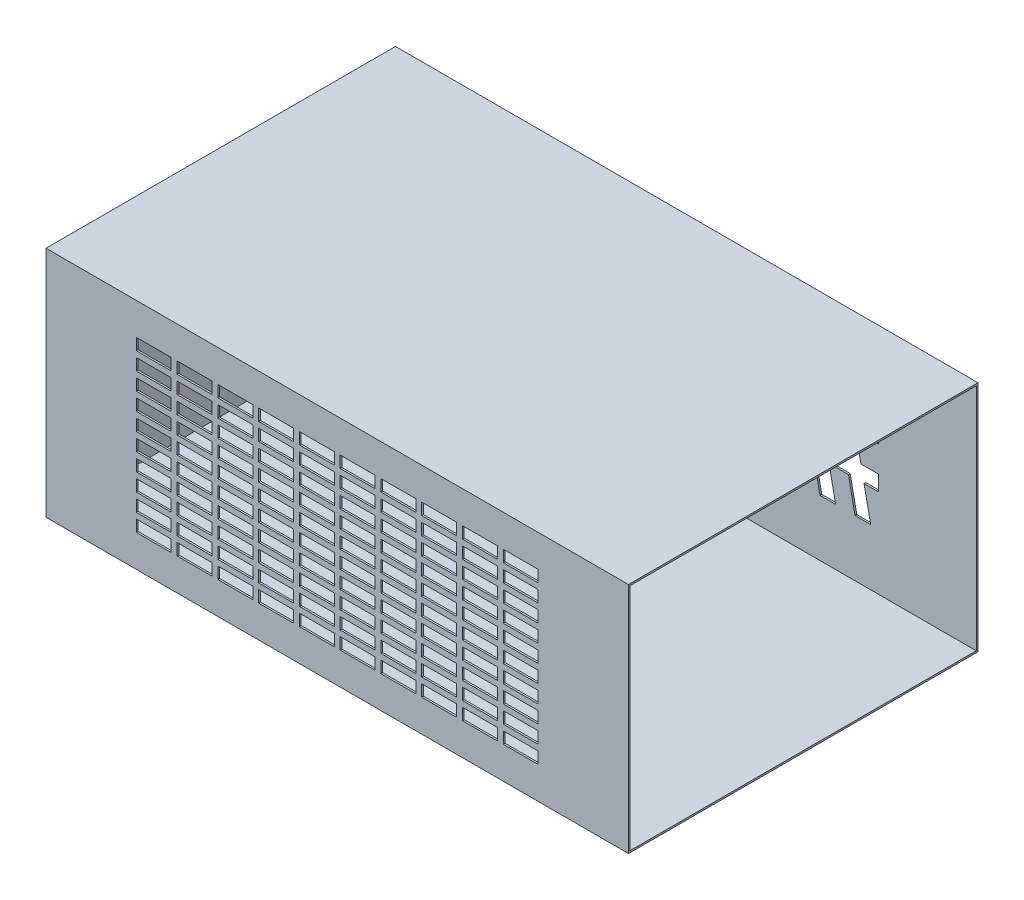
SolidWorks part; units mm, degrees
ref_plane "Спереди" through (0, 0, 0) normal (0, 0, 1) x (1, 0, 0)
ref_plane "Сверху" through (0, 0, 0) normal (0, 1, 0) x (1, 0, 0)
ref_plane "Справа" through (0, 0, 0) normal (1, 0, 0) x (0, 0, -1)
sketch "Эскиз1" plane through (0, 0, 0) normal (0, 0, 1) x (1, 0, 0)
  line L1 (250, -100) -> (-250, -100)
  line L2 (250, -100) -> (250, 100)
  line L3 (250, 100) -> (-250, 100)
  line L4 (-250, -100) -> (-250, 100)
  line L5 (250, -100) -> (-250, 100) construction
  line L6 (250, 100) -> (-250, -100) construction
  point P0 (0, 0)
  dimension "D1" = 500
  dimension "D2" = 200
extrude "Бобышка-Вытянуть2" add sketch "Эскиз1" along normal mid plane 300
shell "Оболочка3" thickness 1.5
sketch "Эскиз5" plane through (0, 0, 150) normal (0, 0, 1) x (1, 0, 0)
  line L0 (250, 100) -> (-250, 100) construction
  line L1 (-172.5, 72.5) -> (-142.5, 72.5)
  line L2 (-172.5, 72.5) -> (-172.5, 62.5)
  line L3 (-172.5, 62.5) -> (-142.5, 62.5)
  line L4 (-142.5, 72.5) -> (-142.5, 62.5)
  line L5 (-250, 100) -> (-250, -100) construction
  dimension "D1" = 30
  dimension "D2" = 10
  dimension "D3" = 27.5
  dimension "D4" = 77.5
extrude "Вырез-Вытянуть1" cut sketch "Эскиз5" against normal up to next
pattern_linear "Линейный массив1" count 10 spacing 35 along (1, 0, 0) count 10 spacing 15 along (0, -1, 0) of "Вырез-Вытянуть1"
sketch "Эскиз8" plane through (0, 0, -150) normal (0, 0, -1) x (-1, 0, 0)
  line L0 (-250, -50) -> (250, -50) construction
  line L5 (250, -100) -> (-250, -100) construction
  line L7 (-250, -100) -> (-250, 100) construction
  line L8 (250, 100) -> (250, -100) construction
  text T0 "#0FF" font "Arial" height in points 400
  point P0 (0, 0)
  dimension "D1" = 50
extrude "Вырез-Вытянуть3" cut sketch "Эскиз8" against normal blind 1.5
